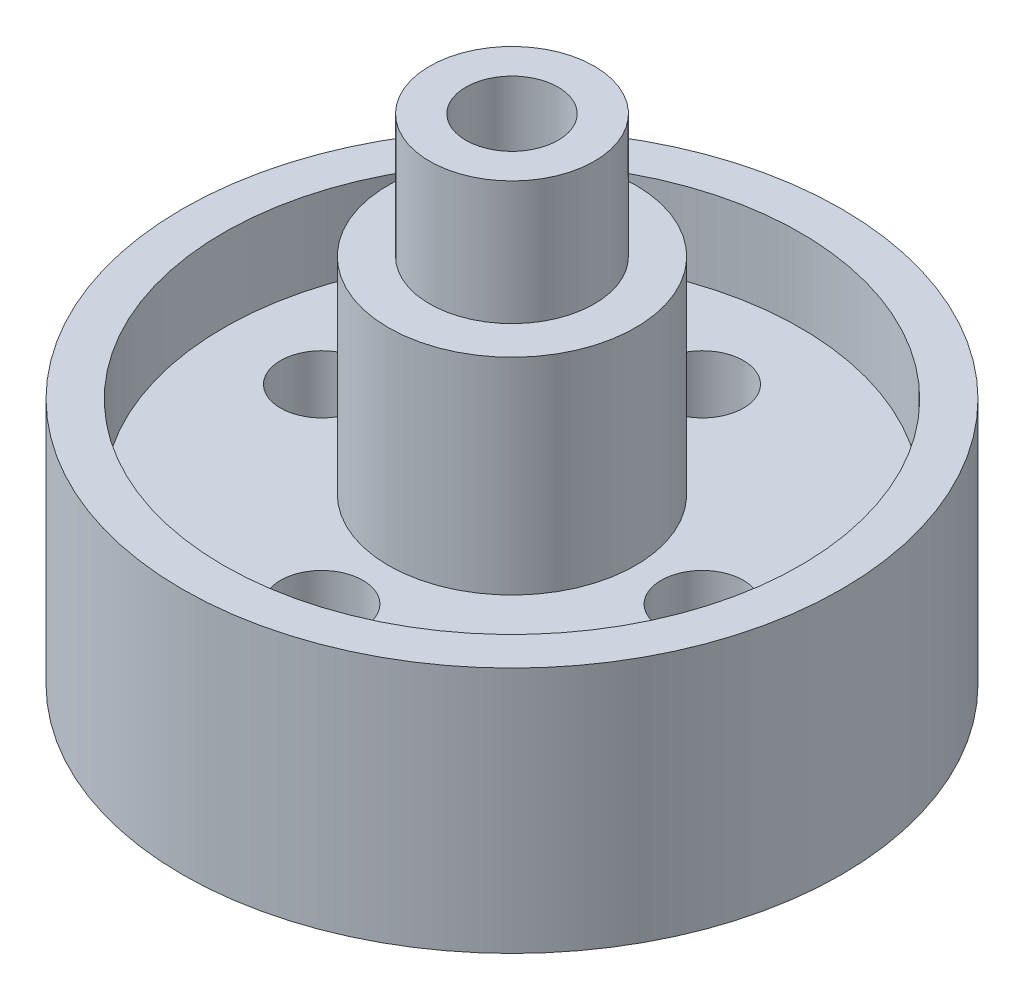
SolidWorks part; units mm, degrees
ref_plane "Front Plane" through (0, 0, 0) normal (0, 0, 1) x (1, 0, 0)
ref_plane "Top Plane" through (0, 0, 0) normal (0, 1, 0) x (1, 0, 0)
ref_plane "Right Plane" through (0, 0, 0) normal (1, 0, 0) x (0, 0, -1)
sketch "Sketch1" plane through (0, 0, 0) normal (0, 1, 0) x (1, 0, 0)
  circle A0 centre (0, 0) radius 50.8
  dimension "D1" = 101.6
extrude "Boss-Extrude2" add sketch "Sketch1" along normal blind 38.1
sketch "Sketch2" plane through (0, 38.1, 0) normal (0, 1, 0) x (1, 0, 0)
  circle A0 centre (0, 0) radius 44.45
  dimension "D1" = 88.9
extrude "Cut-Extrude1" cut sketch "Sketch2" against normal blind 12.7
sketch "Sketch3" plane through (0, 25.4, 0) normal (0, 1, 0) x (1, 0, 0)
  circle A0 centre (0, 0) radius 19.05
  dimension "D1" = 38.1
extrude "Boss-Extrude3" add sketch "Sketch3" along normal blind 31.75
sketch "Sketch4" plane through (0, 57.15, 0) normal (0, 1, 0) x (1, 0, 0)
  circle A0 centre (0, 0) radius 12.7
  dimension "D1" = 25.4
extrude "Boss-Extrude4" add sketch "Sketch4" along normal blind 19.05
sketch "Sketch5" plane through (0, 76.2, 0) normal (0, 1, 0) x (1, 0, 0)
  circle A0 centre (0, 0) radius 7.112
  dimension "D1" = 14.224
extrude "Cut-Extrude2" cut sketch "Sketch5" against normal through all
sketch "Sketch6" plane through (0, 25.4, 0) normal (0, 1, 0) x (1, 0, 0)
  circle A0 centre (0, 0) radius 29.337 construction
  circle A1 centre (0, -29.337) radius 6.35
  circle A2 centre (-29.337, 0) radius 6.35
  circle A3 centre (0, 29.337) radius 6.35
  circle A4 centre (29.337, 0) radius 6.35
  point P14 (0, 0)
  dimension "D1" = 58.674
  dimension "D2" = 12.7
  dimension "D3" = 4
extrude "Cut-Extrude3" cut sketch "Sketch6" against normal through all
